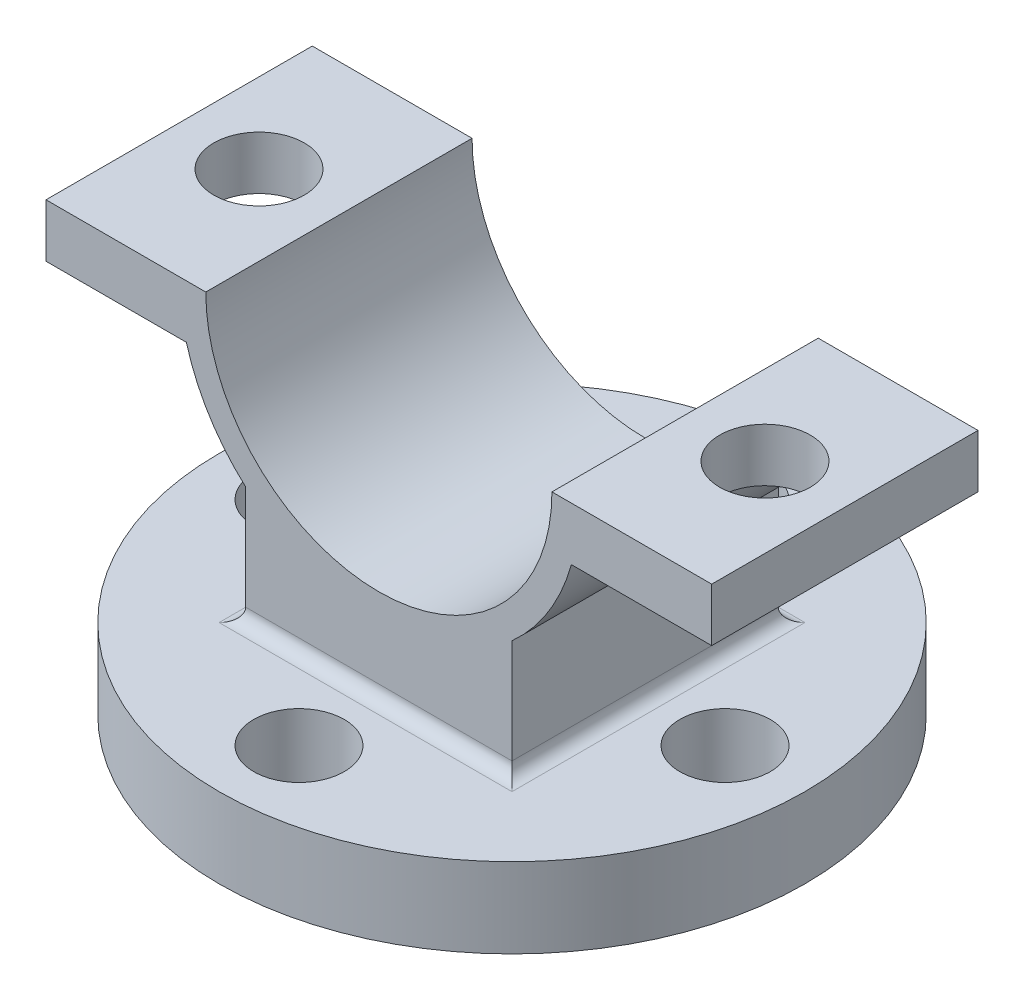
SolidWorks part; units mm, degrees
ref_plane "前视基准面" through (0, 0, 0) normal (0, 0, 1) x (1, 0, 0)
ref_plane "上视基准面" through (0, 0, 0) normal (0, 1, 0) x (1, 0, 0)
ref_plane "右视基准面" through (0, 0, 0) normal (1, 0, 0) x (0, 0, -1)
other "Configuration Table"
sketch "草图1" plane through (0, 0, 0) normal (0, 0, 1) x (1, 0, 0)
  line L0 (5, 0) -> (-5, 0)
  line L1 (-5, 0) -> (-5, 4.4098)
  line L2 (0, 0) -> (0, 35.9785) construction
  line L3 (5, 0) -> (5, 4.4098)
  line L4 (-16.5969, 10) -> (15.1538, 10) construction
  line L5 (-6.5, 10) -> (-12.5, 10)
  line L6 (-12.5, 10) -> (-12.5, 8)
  line L7 (-12.5, 8) -> (-7.2284, 8)
  line L8 (12.5, 10) -> (12.5, 8)
  line L9 (6.5, 10) -> (12.5, 10)
  line L10 (12.5, 8) -> (7.2284, 8)
  arc A0 (5, 4.4098) -> (7.2284, 8) centre (0, 10) ccw
  arc A1 (-7.2284, 8) -> (-5, 4.4098) centre (0, 10) ccw
  arc A2 (-6.5, 10) -> (6.5, 10) centre (0, 10) ccw
  dimension "D2" = 1
  dimension "D4" = 13
  dimension "D1" = 10
  dimension "D3" = 10
  dimension "D5" = 2
  dimension "D6" = 25
extrude "凸台-拉伸1" add sketch "草图1" along normal mid plane 10
sketch "草图2" plane through (0, 0, 0) normal (0, -1, 0) x (1, 0, 0)
  circle A0 centre (0, 0) radius 11
  dimension "D1" = 22
extrude "凸台-拉伸2" add sketch "草图2" along normal blind 3
sketch "草图3" plane through (0, -3, 0) normal (0, -1, 0) x (1, 0, 0)
  circle A0 centre (0, 8) radius 1.7
  circle A1 centre (8, 0) radius 1.7
  circle A2 centre (0, -8) radius 1.7
  circle A3 centre (-8, 0) radius 1.7
  point P12 (0, 0)
  dimension "D2" = 3.4
  dimension "D1" = 8
  dimension "D3" = 4
extrude "切除-拉伸1" cut sketch "草图3" against normal blind 3
fillet "圆角1" radius 0.5 4 edges at (-5, 0, 0) (0, 0, -5) (5, 0, 0) (0, 0, 5)
sketch "草图4" plane through (0, 10, 0) normal (0, 1, 0) x (1, 0, 0)
  line L0 (-9.5, 5) -> (-9.5, -5) construction
  line L1 (-6.5, 5) -> (-12.5, 5) construction
  line L2 (-6.5, -5) -> (-12.5, -5) construction
  line L3 (0, 2.1654) -> (0, -1.6005) construction
  line L4 (9.5, 5) -> (9.5, -5) construction
  circle A0 centre (-9.5, 0) radius 1.7
  circle A1 centre (9.5, 0) radius 1.7
  point P6 (0, 0)
  dimension "D1" = 3.4
extrude "切除-拉伸2" cut sketch "草图4" against normal up to next
